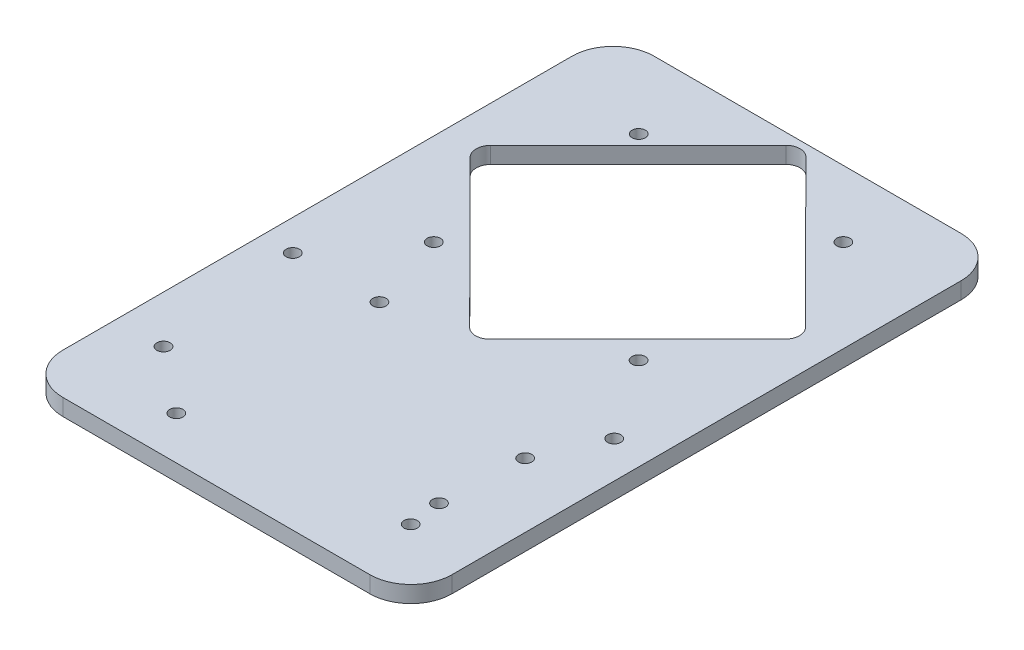
SolidWorks part; units mm, degrees
ref_plane "Front Plane" through (0, 0, 0) normal (0, 0, 1) x (1, 0, 0)
ref_plane "Top Plane" through (0, 0, 0) normal (0, 1, 0) x (1, 0, 0)
ref_plane "Right Plane" through (0, 0, 0) normal (1, 0, 0) x (0, 0, -1)
sketch "Sketch1" plane through (0, 0, 0) normal (0, 1, 0) x (1, 0, 0)
  line L0 (-175.9156, 142.6571) -> (-117.135, 142.6608)
  line L1 (-109.2976, 134.8092) -> (-109.2976, 37.3705)
  line L2 (-176.7986, 112.2097) -> (-148.5316, 140.4928)
  line L8 (-183.7531, 37.367) -> (-183.7532, 37.2565)
  line L9 (-175.9156, 29.519) -> (-117.1491, 29.519)
  line L10 (-183.7531, 134.8055) -> (-183.7531, 37.367)
  line L16 (-176.8012, 108.3505) -> (-148.5692, 80.0323)
  line L17 (-144.7168, 80.0299) -> (-116.45, 108.313)
  line L18 (-116.3523, 112.0717) -> (-116.4476, 112.1722)
  line L19 (-116.4476, 112.1722) -> (-144.6796, 140.4904)
  arc A0 (-183.7531, 134.8055) -> (-175.9156, 142.6571) centre (-175.9016, 134.8055) cw
  arc A1 (-117.135, 142.6608) -> (-109.2976, 134.8092) centre (-117.135, 134.8233) cw
  arc A2 (-109.2976, 37.3705) -> (-117.1491, 29.519) centre (-117.1491, 37.3705) cw
  arc A3 (-175.9156, 29.519) -> (-183.7531, 37.367) centre (-175.9156, 37.3565) cw
  arc A4 (-176.7986, 112.2097) -> (-176.8012, 108.3505) centre (-174.7341, 110.2787) ccw
  arc A5 (-148.5692, 80.0323) -> (-144.7168, 80.0299) centre (-146.6418, 81.9538) ccw
  arc A6 (-116.45, 108.313) -> (-116.4476, 112.1722) centre (-118.3819, 110.2438) ccw
  arc A7 (-144.6796, 140.4904) -> (-148.5316, 140.4928) centre (-146.6068, 138.5691) ccw
  circle A8 centre (-162.4353, 37.7632) radius 1.27
  circle A9 centre (-121.6023, 41.7674) radius 1.27
  circle A10 centre (-122.3798, 47.9761) radius 1.27
  circle A11 centre (-174.7181, 47.5835) radius 1.27
  circle A12 centre (-177.8531, 75.4567) radius 1.27
  circle A13 centre (-161.4165, 75.6081) radius 1.27
  circle A14 centre (-121.6023, 63.6734) radius 1.27
  circle A15 centre (-116.3294, 75.4567) radius 1.27
  circle A16 centre (-126.973, 90.7615) radius 1.27
  circle A17 centre (-166.1599, 90.7612) radius 1.27
  circle A18 centre (-164.473, 128.292) radius 1.27
  circle A19 centre (-126.973, 129.9578) radius 1.27
  point P8 (-164.473, 128.292)
  point P9 (-126.973, 129.9578)
  point P10 (-126.973, 90.7615)
  point P11 (-166.1599, 90.7612)
  point P12 (-177.8531, 75.4567)
  point P13 (-161.4165, 75.6081)
  point P14 (-116.3294, 75.4567)
  point P15 (-121.6023, 63.6734)
  point P16 (-174.7181, 47.5835)
  point P17 (-162.4353, 37.7632)
  point P18 (-121.6023, 41.7674)
  point P19 (-122.3798, 47.9761)
  dimension "D1" = 2.54
extrude "Boss-Extrude2" add sketch "Sketch1" along normal blind 3.175 contours A3 L9 A2 L1 A1 L0 A0 L10 A19 A18 A17 A16 A15 A14 A13 A12 A11 A10 A9 A8 A7 L19 A6 L17 A5 L16 A4 L2
